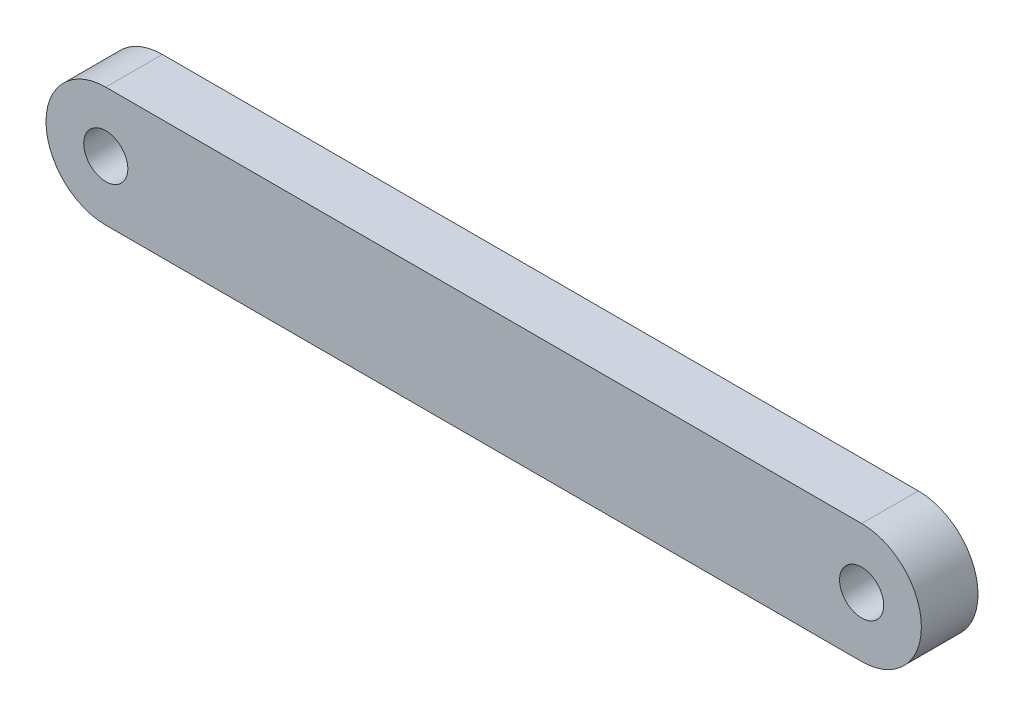
SolidWorks part; units mm, degrees
material "ABS"
ref_plane "Front Plane" through (0, 0, 0) normal (0, 0, 1) x (1, 0, 0)
ref_plane "Top Plane" through (0, 0, 0) normal (0, 1, 0) x (1, 0, 0)
ref_plane "Right Plane" through (0, 0, 0) normal (1, 0, 0) x (0, 0, -1)
sketch "Sketch2" plane through (0, 0, 0) normal (0, 0, -1) x (-1, 0, 0)
  line L0 (-30.0111, 49.9284) -> (30.0111, 49.9284) construction
  line L1 (-30.0111, 54.6746) -> (30.0111, 54.6746)
  line L2 (-30.0111, 45.1823) -> (30.0111, 45.1823)
  arc A0 (-30.0111, 54.6746) -> (-30.0111, 45.1823) centre (-30.0111, 49.9284) ccw
  arc A1 (30.0111, 45.1823) -> (30.0111, 54.6746) centre (30.0111, 49.9284) ccw
  arc A2 (53.7502, -32.8621) -> (-53.7502, -32.8621) centre (0, 0) ccw construction
  circle A3 centre (-30.0111, 49.9284) radius 1.75
  circle A4 centre (30.0111, 49.9284) radius 1.75
  point P4 (0, 49.9284)
  dimension "D1" = 3.5
extrude "Boss-Extrude1" add sketch "Sketch2" along normal blind 4.4958
